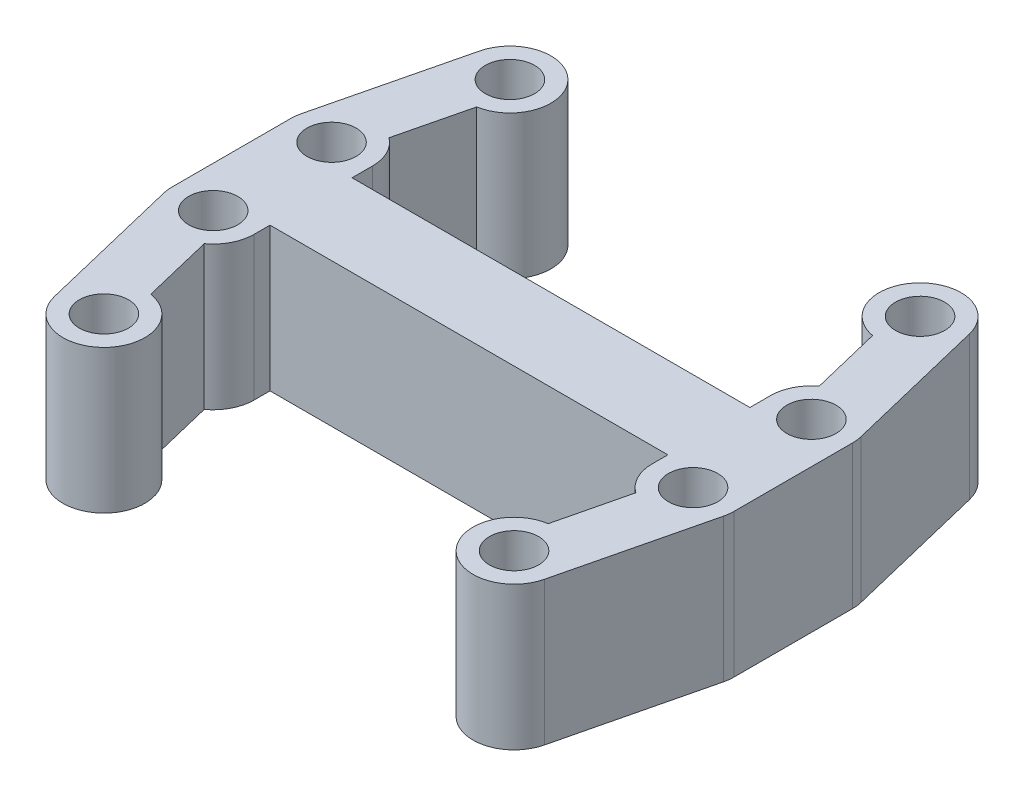
SolidWorks part; units mm, degrees
ref_plane "Front Plane" through (0, 0, 0) normal (0, 0, 1) x (1, 0, 0)
ref_plane "Top Plane" through (0, 0, 0) normal (0, 1, 0) x (1, 0, 0)
ref_plane "Right Plane" through (0, 0, 0) normal (1, 0, 0) x (0, 0, -1)
sketch "Sketch2" plane through (0, 0, 0) normal (0, 1, 0) x (1, 0, 0)
  line L1 (-16.6529, 7.2905) -> (-15.3276, 12.7475)
  line L2 (-18.9603, 16.6243) -> (-21.6591, 5.5118)
  line L3 (-21.7487, 4.7625) -> (-21.7488, -4.3974)
  line L8 (-16.7028, -6.9626) -> (-15.3829, -12.4209)
  line L26 (-18.9611, -16.3038) -> (-21.6598, -5.1436)
  line L29 (0, 10.8515) -> (0, -11.8971) construction
  line L30 (16.6529, 7.2905) -> (15.3276, 12.7475)
  line L31 (18.9603, 16.6243) -> (21.6591, 5.5118)
  line L32 (21.7487, 4.7625) -> (21.7488, -4.3974)
  line L33 (18.9611, -16.3038) -> (21.6598, -5.1436)
  line L34 (16.7028, -6.9626) -> (15.3829, -12.4209)
  line L35 (-15.3988, 4.7625) -> (-15.3988, 3.175)
  line L36 (-15.3988, 3.175) -> (15.3988, 3.175)
  line L37 (-15.3987, -4.3974) -> (-15.3988, -3.175)
  line L38 (-15.3988, -3.175) -> (15.3988, -3.175)
  line L39 (0, 3.175) -> (0, 0) construction
  line L40 (0, 0) -> (0, -3.175) construction
  line L41 (15.3987, -4.3974) -> (15.3988, -3.175)
  line L42 (15.3988, 4.7625) -> (15.3988, 3.175)
  circle A0 centre (-15.875, 15.875) radius 1.905
  arc A1 (-15.3276, 12.7475) -> (-18.9603, 16.6243) centre (-15.875, 15.875) ccw
  circle A2 centre (-18.5738, 4.7625) radius 1.905
  circle A5 centre (-18.5738, -4.3974) radius 1.905
  circle A8 centre (-15.875, -15.5575) radius 1.905
  arc A9 (-15.3988, 4.7625) -> (-16.6529, 7.2905) centre (-18.5738, 4.7625) ccw
  arc A10 (-15.3987, -4.3974) -> (-16.7028, -6.9626) centre (-18.5738, -4.3974) cw
  arc A11 (-15.3829, -12.4209) -> (-18.9611, -16.3038) centre (-15.875, -15.5575) cw
  arc A16 (-21.6591, 5.5118) -> (-21.7487, 4.7625) centre (-18.5738, 4.7625) ccw
  arc A17 (-21.7488, -4.3974) -> (-21.6598, -5.1436) centre (-18.5738, -4.3974) ccw
  arc A18 (15.3988, 4.7625) -> (16.6529, 7.2905) centre (18.5738, 4.7625) cw
  arc A19 (15.3276, 12.7475) -> (18.9603, 16.6243) centre (15.875, 15.875) cw
  arc A20 (21.6591, 5.5118) -> (21.7487, 4.7625) centre (18.5738, 4.7625) cw
  arc A21 (21.7488, -4.3974) -> (21.6598, -5.1436) centre (18.5738, -4.3974) cw
  arc A22 (15.3987, -4.3974) -> (16.7028, -6.9626) centre (18.5738, -4.3974) ccw
  arc A23 (15.3829, -12.4209) -> (18.9611, -16.3038) centre (15.875, -15.5575) ccw
  circle A24 centre (15.875, -15.5575) radius 1.905
  circle A25 centre (18.5738, -4.3974) radius 1.905
  circle A26 centre (18.5738, 4.7625) radius 1.905
  circle A27 centre (15.875, 15.875) radius 1.905
  point P37 (0, -4.3974)
  dimension "D1" = 3.81
  dimension "D2" = 3.175
  dimension "D3" = 3.175
  dimension "D4" = 15.875
  dimension "D5" = 15.875
  dimension "D6" = 15.5575
  dimension "D7" = 4.7625
  dimension "D8" = 18.5738
  dimension "D9" = 4.3974
  dimension "D10" = 4.445
  dimension "D11" = 6.35
extrude "Boss-Extrude1" add sketch "Sketch2" along normal blind 11.1125
